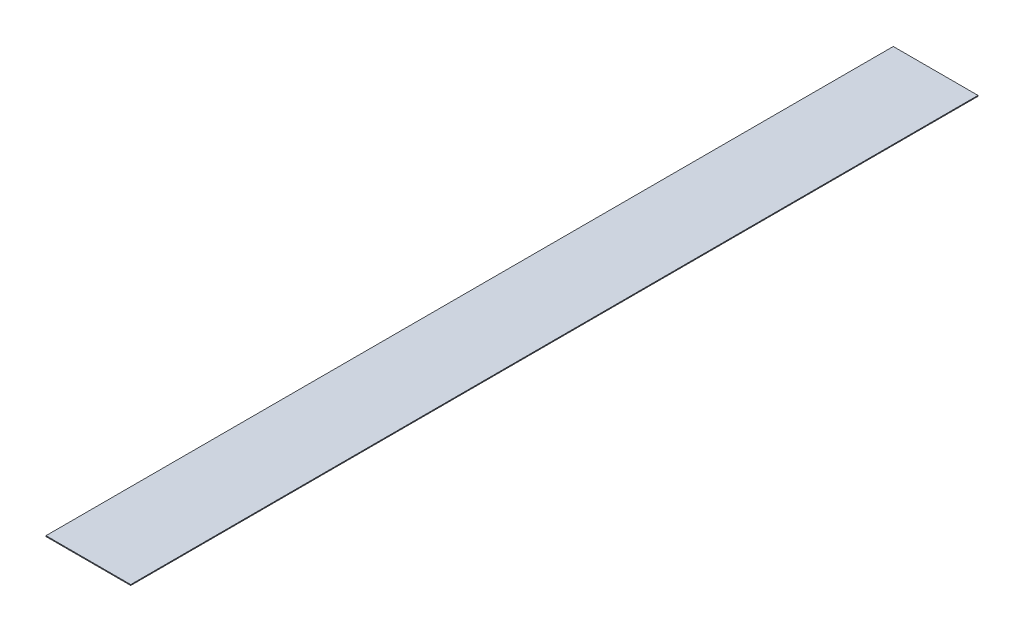
SolidWorks part; units mm, degrees
ref_plane "Front Plane" through (0, 0, 0) normal (0, 0, 1) x (1, 0, 0)
ref_plane "Top Plane" through (0, 0, 0) normal (0, 1, 0) x (1, 0, 0)
ref_plane "Right Plane" through (0, 0, 0) normal (1, 0, 0) x (0, 0, -1)
sketch "Sketch1" plane through (0, 0, 0) normal (0, 1, 0) x (1, 0, 0)
  line L1 (0, 0) -> (1000, 0)
  line L2 (0, 0) -> (0, 10000)
  line L3 (0, 10000) -> (1000, 10000)
  line L4 (1000, 0) -> (1000, 10000)
  dimension "D1" = 1000
  dimension "D2" = 10000
extrude "Boss-Extrude1" add sketch "Sketch1" along normal blind 10
